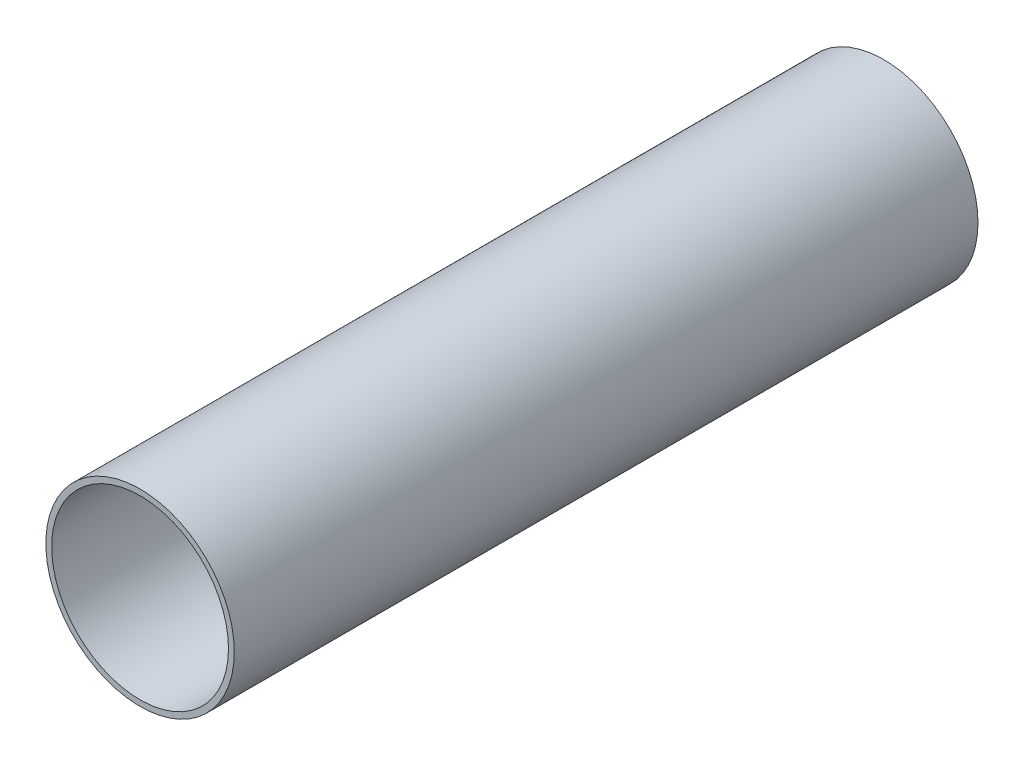
SolidWorks part; units mm, degrees
material "E-Glass Fiber"
ref_plane "Front Plane" through (0, 0, 0) normal (0, 0, 1) x (1, 0, 0)
ref_plane "Top Plane" through (0, 0, 0) normal (0, 1, 0) x (1, 0, 0)
ref_plane "Right Plane" through (0, 0, 0) normal (1, 0, 0) x (0, 0, -1)
sketch "Sketch1" plane through (0, 0, 0) normal (0, 0, 1) x (1, 0, 0)
  circle A0 centre (0, 0) radius 34.671
  circle A1 centre (0, 0) radius 32.5374
  dimension "D1" = 69.342
  dimension "D2" = 65.0748
extrude "Boss-Extrude1" add sketch "Sketch1" along normal blind 273.685
